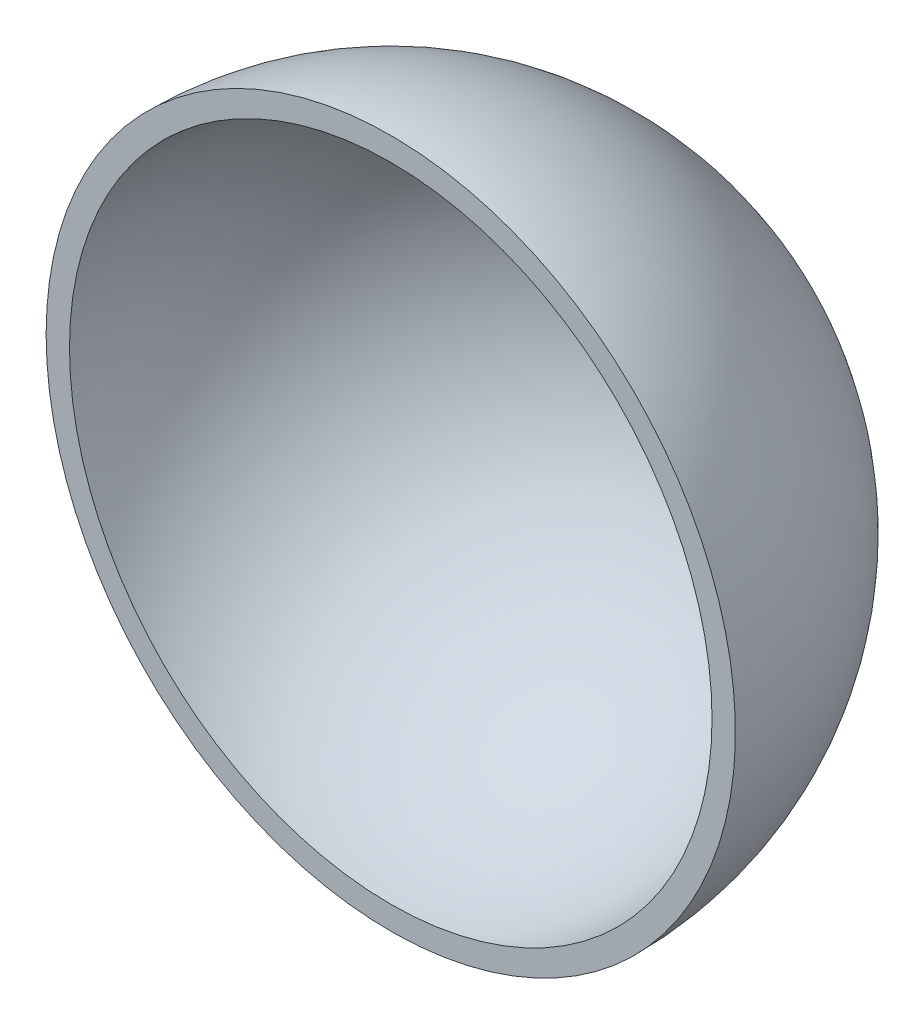
SolidWorks part; units mm, degrees
ref_plane "Front Plane" through (0, 0, 0) normal (0, 0, 1) x (1, 0, 0)
ref_plane "Top Plane" through (0, 0, 0) normal (0, 1, 0) x (1, 0, 0)
ref_plane "Right Plane" through (0, 0, 0) normal (1, 0, 0) x (0, 0, -1)
sketch "Sketch1" plane through (0, 0, 0) normal (0, 0, 1) x (1, 0, 0)
  line L0 (-118, 0) -> (118, 0) construction
  arc A0 (118, 0) -> (-118, 0) centre (0, 0) cw
revolve "Revolve-Thin1" add sketch "Sketch1" angle 180 about L0
